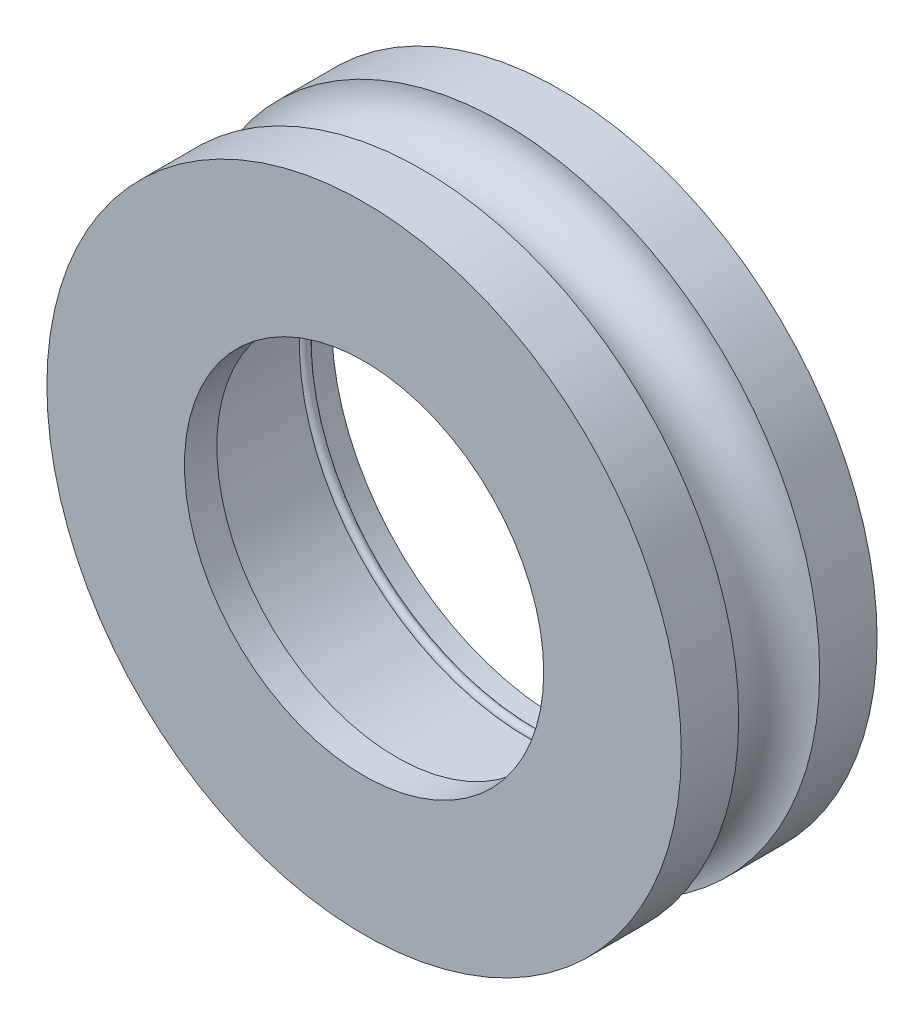
SolidWorks part; units mm, degrees
ref_plane "Alzado" through (0, 0, 0) normal (0, 0, 1) x (1, 0, 0)
ref_plane "Planta" through (0, 0, 0) normal (0, 1, 0) x (1, 0, 0)
ref_plane "Vista lateral" through (0, 0, 0) normal (1, 0, 0) x (0, 0, -1)
sketch "Croquis1" plane through (0, 0, 0) normal (0, 0, 1) x (1, 0, 0)
  circle A0 centre (0, 0) radius 11.1
  circle A1 centre (0, 0) radius 14.1
  circle A3 centre (0, 0) radius 14 construction
  dimension "D1" = 3
  dimension "D2" = 0.1
extrude "Saliente-Extruir1" add sketch "Croquis1" along normal blind 2
sketch "Croquis4" plane through (0, 0, 0) normal (0, 1, 0) x (1, 0, 0)
  line L0 (14.1, -2) -> (14.1, 0)
  line L1 (14.1, 0) -> (14.1, 8.1)
  line L3 (14.1, 10.1) -> (19.6, 10.1)
  line L4 (19.6, 10.1) -> (19.6, 6.55)
  line L5 (19.6, 1.55) -> (19.6, -2)
  line L6 (19.6, -2) -> (14.1, -2)
  line L7 (17.1, 4.05) -> (14.1, 4.05) construction
  line L8 (0, 0) -> (0, 8) construction
  line L9 (14.1, 10.1) -> (14.1, 8.1) construction
  line L10 (14, 8) -> (-14, 8) construction
  line L11 (14.1, 8.7) -> (14.1, 10.1)
  arc A0 (19.6, 6.55) -> (19.6, 1.55) centre (19.6, 4.05) ccw
  arc A2 (14.1, 8.1) -> (14.1, 8.7) centre (14.1, 8.4) cw
  dimension "D3" = 0.3
  dimension "D1" = 5
  dimension "D2" = 3
  dimension "D4" = 0.1
revolve "Revolución1" add sketch "Croquis4" angle 360 about L8
sketch "Croquis5" plane through (0, 0, 0) normal (0, 1, 0) x (1, 0, 0)
  line L0 (17.1, 4.05) -> (-17.1, 4.05) construction
  arc A0 (19.6, 6.55) -> (19.6, 1.55) centre (19.6, 4.05) ccw construction
  arc A1 (-19.6, 1.55) -> (-19.6, 6.55) centre (-19.6, 4.05) ccw construction
sketch "Croquis6" plane through (0, 0, 0) normal (0, 0, 1) x (1, 0, 0)
  line L1 (-17.1, 0) -> (17.1, 0) construction
  line L2 (17.1, 0) -> (-17.1, 0) construction
  line L4 (17.1, 17.1) -> (-17.1, 17.1)
  line L5 (17.1, 17.1) -> (17.1, -17.1)
  line L6 (17.1, -17.1) -> (-17.1, -17.1)
  line L7 (-17.1, 17.1) -> (-17.1, -17.1)
  line L8 (17.1, 17.1) -> (-17.1, -17.1) construction
  line L9 (17.1, -17.1) -> (-17.1, 17.1) construction
  circle A0 centre (0, 0) radius 17.1
sketch "Croquis7" plane through (0, 0, -10.1) normal (0, 0, -1) x (-1, 0, 0)
  line L0 (0, 0) -> (0, 14.1) construction
  line L1 (0, 14.1) -> (0, 19.6) construction
  line L2 (14.5925, 6.6929) -> (16.0925, 9.291)
  line L3 (1.5, 15.984) -> (0, 18.5821)
  line L4 (0, 18.5821) -> (-1.5, 15.984)
  line L5 (-1.5, 15.984) -> (1.5, 15.984)
  line L6 (16.0925, 9.291) -> (13.0925, 9.291)
  line L7 (13.0925, 9.291) -> (14.5925, 6.6929)
  line L8 (13.0925, -9.291) -> (16.0925, -9.291)
  line L9 (16.0925, -9.291) -> (14.5925, -6.6929)
  line L10 (14.5925, -6.6929) -> (13.0925, -9.291)
  line L11 (-1.5, -15.984) -> (0, -18.5821)
  line L12 (0, -18.5821) -> (1.5, -15.984)
  line L13 (1.5, -15.984) -> (-1.5, -15.984)
  line L14 (-14.5925, -6.6929) -> (-16.0925, -9.291)
  line L15 (-16.0925, -9.291) -> (-13.0925, -9.291)
  line L16 (-13.0925, -9.291) -> (-14.5925, -6.6929)
  line L17 (-13.0925, 9.291) -> (-16.0925, 9.291)
  line L18 (-16.0925, 9.291) -> (-14.5925, 6.6929)
  line L19 (-14.5925, 6.6929) -> (-13.0925, 9.291)
  circle A1 centre (0, 0) radius 19.6 construction
  circle A2 centre (0, 16.85) radius 0.866 construction
  circle A3 centre (0, 0) radius 14.1 construction
  point P32 (0, 0)
  dimension "D1" = 3
  dimension "D2" = 6
extrude "Cortar-Extruir1" cut sketch "Croquis7" against normal blind 1
